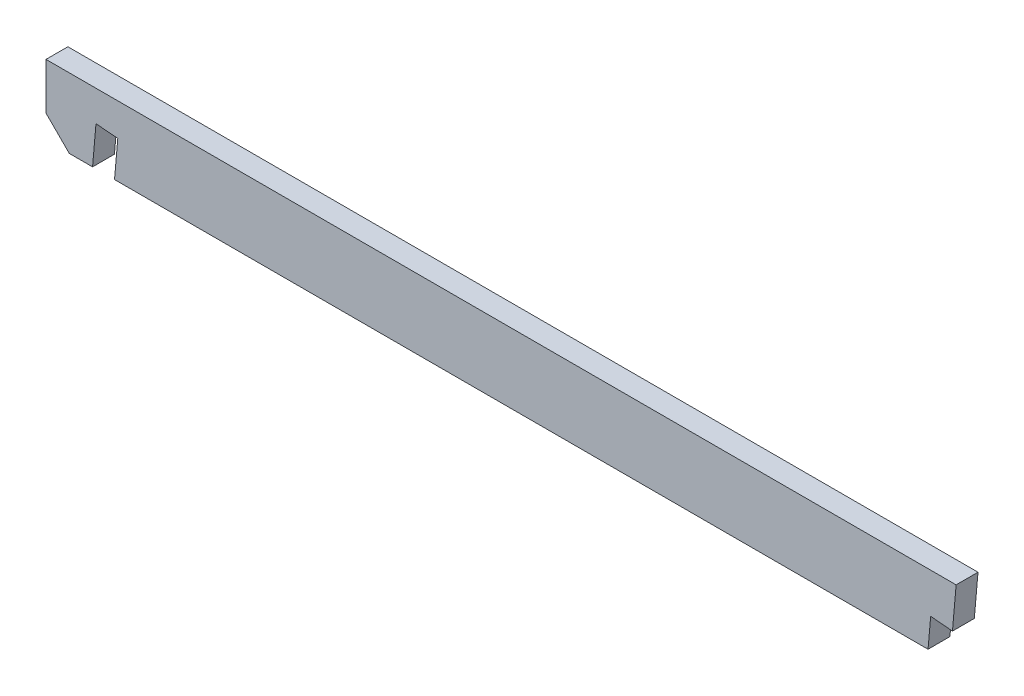
SolidWorks part; units mm, degrees
ref_plane "Front Plane" through (0, 0, 0) normal (0, 0, 1) x (1, 0, 0)
ref_plane "Top Plane" through (0, 0, 0) normal (0, 1, 0) x (1, 0, 0)
ref_plane "Right Plane" through (0, 0, 0) normal (1, 0, 0) x (0, 0, -1)
sketch "Sketch1" plane through (0, 0, 0) normal (1, 0, 0) x (0, 0, -1)
  line L1 (-23.5, -75) -> (23.5, -75)
  line L2 (-23.5, -75) -> (-23.5, 75)
  line L3 (-23.5, 75) -> (23.5, 75)
  line L4 (23.5, -75) -> (23.5, 75)
  line L5 (-23.5, -75) -> (23.5, 75) construction
  line L6 (-23.5, 75) -> (23.5, -75) construction
  point P0 (0, 0)
  dimension "D1" = 47
  dimension "D2" = 150
extrude "Boss-Extrude1" add sketch "Sketch1" along normal blind 1955
sketch "Sketch2" plane through (0, 0, 23.5) normal (0, 0, 1) x (1, 0, 0)
  line L0 (100, -75) -> (107.3575, 9.0963)
  line L1 (1955, -75) -> (0, -75) construction
  line L2 (107.3575, 9.0963) -> (154.1786, 5)
  line L3 (154.1786, 5) -> (147.1795, -75)
  line L4 (0, 75) -> (0, -75) construction
  line L5 (100, -75) -> (147.1795, -75)
  dimension "D1" = 47
  dimension "D2" = 5
  dimension "D3" = 80
  dimension "D4" = 100
extrude "Cut-Extrude1" cut sketch "Sketch2" against normal through all
chamfer "Chamfer1" distance 50 angle 45 1 edges at (0, -75, 0)
sketch "Sketch3" plane through (0, 0, -23.5) normal (0, 0, -1) x (-1, 0, 0)
  line L0 (-1955, 75) -> (-1941.8767, -75)
  line L1 (-1955, -75) -> (-147.1795, -75) construction
  line L2 (-1941.8767, -75) -> (-1955, -75)
  line L3 (-1955, -75) -> (-1955, 75)
  dimension "D1" = 5
extrude "Cut-Extrude2" cut sketch "Sketch3" against normal through all
sketch "Sketch4" plane through (0, 0, 23.5) normal (0, 0, 1) x (1, 0, 0)
  line L0 (1947.126, -15) -> (1900.3049, -10.9037)
  line L1 (1941.8767, -75) -> (1955, 75) construction
  line L2 (1900.3049, -10.9037) -> (1894.6972, -75)
  line L3 (1941.8767, -75) -> (147.1795, -75) construction
  line L4 (1894.6972, -75) -> (1941.8767, -75)
  line L5 (1941.8767, -75) -> (1947.126, -15)
  dimension "D1" = 60
  dimension "D2" = 47
extrude "Cut-Extrude3" cut sketch "Sketch4" against normal through all
